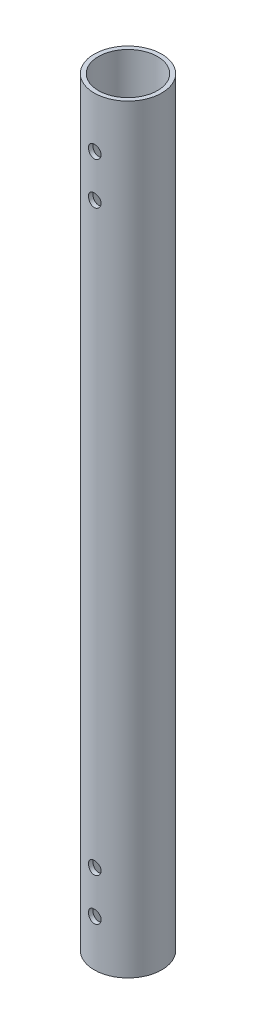
SolidWorks part; units mm, degrees
material "Hexcel AS4C (3000 Filaments)"
ref_plane "Ön Düzlem" through (0, 0, 0) normal (0, 0, 1) x (1, 0, 0)
ref_plane "Üst Düzlem" through (0, 0, 0) normal (0, 1, 0) x (1, 0, 0)
ref_plane "Sağ Düzlem" through (0, 0, 0) normal (1, 0, 0) x (0, 0, -1)
sketch "Çizim1" plane through (0, 0, 0) normal (0, 1, 0) x (1, 0, 0)
  circle A0 centre (0, 0) radius 8
  circle A1 centre (0, 0) radius 7
  dimension "D1" = 14
  dimension "D2" = 16
extrude "Yükseklik-Ekstrüzyon1" add sketch "Çizim1" along normal blind 180
sketch "Çizim2" plane through (0, 0, 0) normal (0, 0, 1) x (1, 0, 0)
  line L0 (7, 180) -> (-7, 180) construction
  line L1 (0, 180) -> (0, 150.69) construction
  line L2 (8, 180) -> (-8, 180) construction
  circle A0 centre (0, 11) radius 1.5
  circle A1 centre (0, 168) radius 1.5
  circle A2 centre (0, 158) radius 1.5
  circle A3 centre (0, 21) radius 1.5
  dimension "D2" = 3
  dimension "D3" = 3
  dimension "D4" = 22
  dimension "D1" = 11
  dimension "D5" = 10
  dimension "D6" = 10
extrude "Kes-Ekstrüzyon1" cut sketch "Çizim2" against normal mid plane 20
